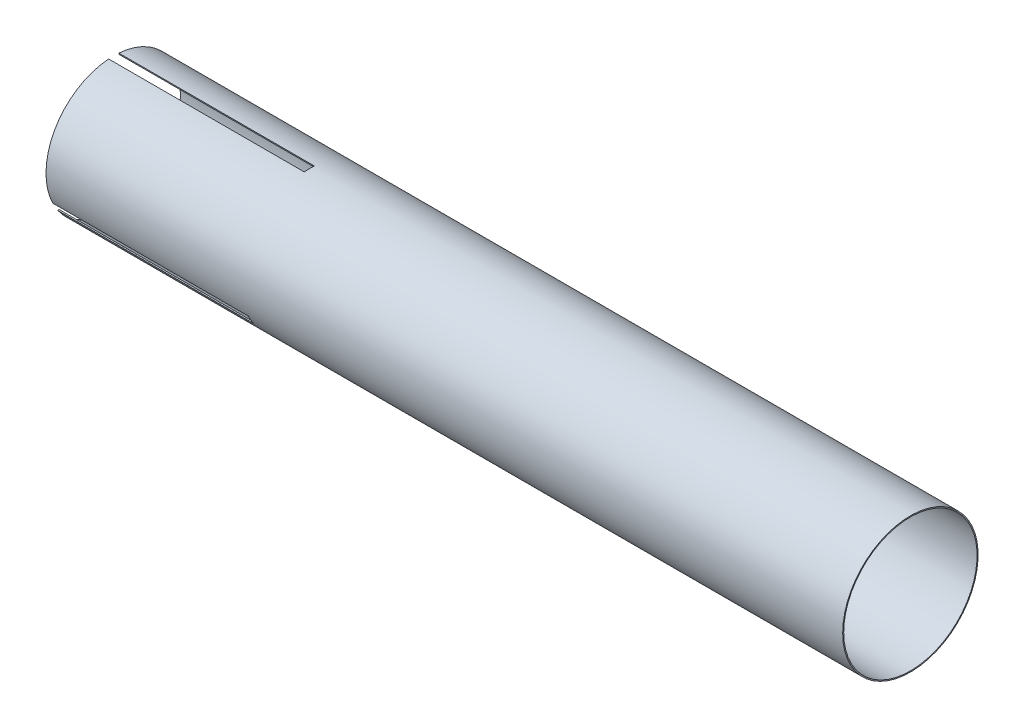
SolidWorks part; units mm, degrees
ref_plane "Plan de face" through (0, 0, 0) normal (0, 0, 1) x (1, 0, 0)
ref_plane "Plan de dessus" through (0, 0, 0) normal (0, 1, 0) x (1, 0, 0)
ref_plane "Plan de droite" through (0, 0, 0) normal (1, 0, 0) x (0, 0, -1)
sketch "Esquisse1" plane through (0, 0, 0) normal (0, 0, 1) x (1, 0, 0)
  line L0 (0, 0) -> (0, 76.182) construction
  line L1 (0, 0) -> (142.5133, 0) construction
  line L2 (0, 76.182) -> (896, 76.182)
  line L3 (0, 76.182) -> (0, -76.182) construction
  line L4 (0, 75) -> (896, 75)
  line L5 (896, 76.182) -> (896, 75)
  line L6 (0, -76.182) -> (896, -76.182) construction
  line L7 (0, 76.182) -> (0, 75)
  dimension "D1" = 152.364
  dimension "D3" = 896
  dimension "D2" = 150
revolve "Révolution1" add sketch "Esquisse1" angle 360 about L1
sketch "Esquisse2" plane through (0, 0, 0) normal (0, 1, 0) x (1, 0, 0)
  line L0 (0, 76.182) -> (0, -76.182) construction
  line L1 (0, -5.741) -> (220, -5.741)
  line L2 (0, -5.741) -> (0, 5.741)
  line L3 (0, 5.741) -> (220, 5.741)
  line L4 (220, -5.741) -> (220, 5.741)
  dimension "D1" = 11.482
  dimension "D2" = 220
extrude "Enlèv. mat.-Extru.1" cut sketch "Esquisse2" along normal through all
pattern_circular "Répétition circulaire1" count 3 over 240 about axis through (0, 0, 0) along (1, 0, 0) of "Enlèv. mat.-Extru.1"
equation "\"D1@Esquisse1\"=\"d_i_tube\"+\"t_tube\"*2"
equation "\"d_i_tube\"= 150mm'Inner Rocket Body Composite Tube Diameter"
equation "\"t_tube\"= 1.182mm'Thickness of Rocket Body Composite Tube"
equation "\"l_upper_body_tube\"= 1190mm'Upper Rocket Body Composite Tube length"
equation "\"l_lower_body_tube\"= 896mm'Lower Rocket Body Composite Tube Length"
equation "\"d_a_NC\"= 154mm'Outer Diameter of Nosecone base"
equation "\"d_i_phenolic_tube\"= 152.3mm'Inner Phenolic Tube Diameter"
equation "\"t_phenolic_tube\"= 2mm'Thickness of Phenolic Body Tube"
equation "\"D3@Esquisse1\"=\"l_lower_body_tube\""
equation "\"D2@Esquisse1\"=\"d_i_tube\""
equation "\"l_fin_cut\"= 220mm'Length of fin on Motor Retainer"
equation "\"t_SW-Panel\"= 11.482mm'Thickness of Sandwich-Panel"
equation "\"l_motor_tube\"=650mm'Length of phenolic motor tube"
equation "\"d_i_motor_tube\"=99.06mm'Inner diameter of phenolic motor tube"
equation "\"t_motor_tube\"=1.58mm'Thicknes of phenolic motor tube"
equation "\"l_cut_fin_centering\"=13mm'Length of cut for fin alignement on fin centering rings"
equation "\"D2@Esquisse2\"=\"l_fin_cut\""
equation "\"D1@Esquisse2\"=\"t_SW-Panel\""
